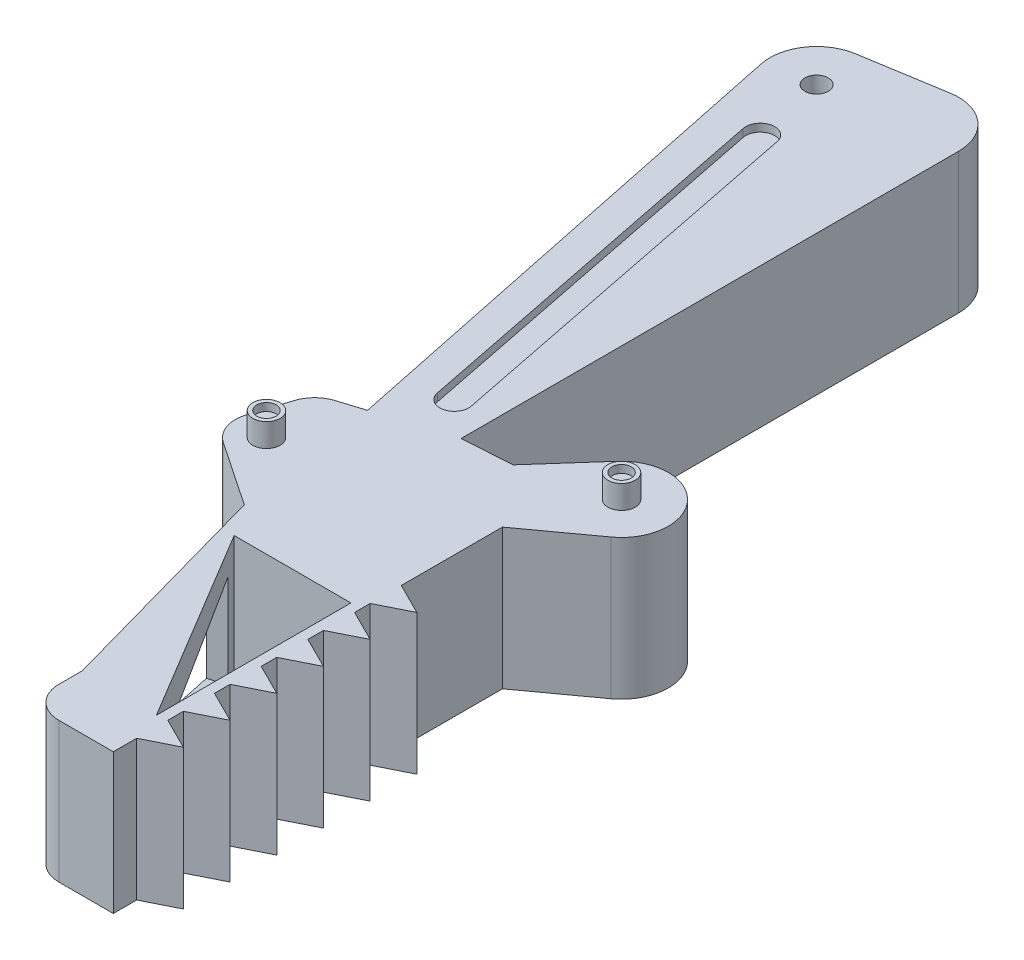
SolidWorks part; units mm, degrees
ref_plane "Front Plane" through (0, 0, 0) normal (0, 0, 1) x (1, 0, 0)
ref_plane "Top Plane" through (0, 0, 0) normal (0, 1, 0) x (1, 0, 0)
ref_plane "Right Plane" through (0, 0, 0) normal (1, 0, 0) x (0, 0, -1)
sketch "Sketch2" plane through (0, 0, 0) normal (0, 1, 0) x (1, 0, 0)
  line L0 (0, 0) -> (-47.8337, 0) construction
  line L4 (-26.3265, -3.8719) -> (-2.6409, 0)
  line L5 (-11.7844, -73.8719) -> (-16.9516, -75.4948)
  line L6 (-16.9516, -75.4948) -> (-19.9749, -85.0269)
  line L7 (-19.9749, -85.0269) -> (-9.1952, -92.2931)
  line L8 (-9.1952, -92.2931) -> (-1.1293, -121.1884)
  line L9 (-1.1293, -121.1884) -> (-1.1293, -128.1884)
  line L10 (-1.1293, -128.1884) -> (9.8707, -128.1884)
  line L11 (9.8707, -128.1884) -> (9.8707, -78.1884)
  line L12 (9.8707, -78.1884) -> (17.9634, -72.3141)
  line L13 (-2.6409, 0) -> (-2.6409, -71)
  line L14 (-2.6409, -71) -> (-11.7844, -73.8719)
  line L15 (-11.7844, -73.8719) -> (-26.3265, -3.8719)
  line L16 (-2.6409, -71) -> (3.6435, -70.5783)
  line L17 (3.6435, -70.5783) -> (9.9527, -63.4743)
  arc A0 (9.9527, -63.4743) -> (17.9634, -72.3141) centre (14.4389, -67.4585) cw
  point P17 (12.9548, -76.5257)
  point P18 (10.1005, -71)
  point P19 (16.4521, -62.391)
  point P20 (17.1505, -78.4257)
  point P22 (11.9758, -79.4186)
  point P23 (11.9386, -62.3885)
  point P24 (10.0167, -77.8819)
  point P25 (-8.9398, -91.899)
  point P26 (-1.1293, -121.1884)
  dimension "D12" = 6
  dimension "D1" = 24
  dimension "D2" = 71
  dimension "D3" = 70
  dimension "D4" = 10
  dimension "D5" = 13
  dimension "D6" = 30
  dimension "D7" = 7
  dimension "D8" = 11
  dimension "D9" = 50
  dimension "D10" = 10
  dimension "D11" = 15
extrude "Boss-Extrude1" add sketch "Sketch2" along normal mid plane 18 contours A0 L17 L16 L14 L5 L6 L7 L8 L9 L10 L11 L12 | L15 L14 L13 L4
fillet "Fillet1" radius 6 2 edges at (-2.6409, 0, 0) (-26.3265, 0, 3.8719)
fillet "Fillet2" radius 4 3 edges at (-1.1293, 0, 128.1884) (-16.9516, 0, 75.4948) (-19.9749, 0, 85.0269)
sketch "Sketch3" plane through (0, 9, 0) normal (0, 1, 0) x (1, 0, 0)
  line L0 (9.8707, -123.1884) -> (13.8707, -123.1884) construction
  line L1 (9.8707, -128.1884) -> (9.8707, -78.1884) construction
  line L2 (2.8707, -128.1884) -> (9.8707, -128.1884) construction
  line L3 (9.8707, -125.1884) -> (9.8707, -121.1884)
  line L4 (9.8707, -121.1884) -> (13.8707, -123.1884)
  line L5 (13.8707, -123.1884) -> (9.8707, -125.1884)
  point P9 (9.8707, -123.1884)
  dimension "D1" = 5
  dimension "D2" = 4
  dimension "D3" = 4
extrude "Boss-Extrude2" add sketch "Sketch3" against normal blind 18
pattern_linear "LPattern1" count 6 spacing 6 along (0, 0, -1) of "Boss-Extrude2"
sketch "Sketch5" plane through (0, 9, 0) normal (0, 1, 0) x (1, 0, 0)
  line L0 (8.5819, -96.3665) -> (-6.4181, -96.3665)
  line L1 (-6.4181, -96.3665) -> (8.5819, -121.3665)
  line L2 (8.5819, -121.3665) -> (8.5819, -96.3665)
  dimension "D1" = 15
  dimension "D2" = 25
extrude "Cut-Extrude1" cut sketch "Sketch5" against normal blind 26
sketch "Sketch6" plane through (-32.431, 0, 9.0528) normal (-0.9632, 0, 0.2689) x (0.2689, 0, 0.9632)
  line L0 (93.4224, 6) -> (93.4224, -6)
  line L1 (93.4224, -6) -> (111.4224, -4.5339)
  line L2 (111.4224, -4.5339) -> (111.4224, 4.5339)
  line L3 (111.4224, 4.5339) -> (93.4224, 6)
  line L4 (86.4224, 9) -> (86.4224, -9) construction
  line L5 (116.4224, 9) -> (116.4224, -9) construction
  line L6 (86.4224, 9) -> (116.4224, 9) construction
  point P6 (86.4224, 0)
  point P7 (93.4224, 0)
  point P10 (116.4224, 0)
  point P11 (111.4224, 0)
  dimension "D1" = 7
  dimension "D2" = 5
  dimension "D3" = 3
extrude "Cut-Extrude2" cut sketch "Sketch6" against normal blind 8
sketch "Sketch7" plane through (0, 9, 0) normal (0, 1, 0) x (1, 0, 0)
  circle A0 centre (-19.1781, -8.783) radius 1.5
  dimension "D1" = 3
extrude "Cut-Extrude3" cut sketch "Sketch7" against normal blind 26
sketch "Sketch8" plane through (0, 9, 0) normal (0, 1, 0) x (1, 0, 0)
  circle A0 centre (14.4389, -67.4585) radius 1.75
  circle A1 centre (-15.2572, -83.3831) radius 1.75
  dimension "D1" = 3.5
extrude "Boss-Extrude3" add sketch "Sketch8" along normal blind 3
sketch "Sketch9" plane through (0, 12, 0) normal (0, 1, 0) x (1, 0, 0)
  circle A2 centre (-15.2572, -83.3831) radius 1.25
  circle A3 centre (-15.2572, -83.3831) radius 1.25
  dimension "D1" = 0.5
extrude "Cut-Extrude4" cut sketch "Sketch9" against normal blind 1
sketch "Sketch10" plane through (0, 12, 0) normal (0, 1, 0) x (1, 0, 0)
  circle A2 centre (14.4389, -67.4585) radius 1.25
  circle A3 centre (14.4389, -67.4585) radius 1.25
  dimension "D1" = 0.5
extrude "Cut-Extrude5" cut sketch "Sketch10" against normal blind 1
sketch "Sketch11" plane through (0, 9, 0) normal (0, 1, 0) x (1, 0, 0)
  line L0 (-17.1966, -18.0056) -> (-7.4101, -67.0949) construction
  line L1 (-15.3753, -17.6425) -> (-5.5888, -66.7318)
  line L2 (-19.0178, -18.3687) -> (-9.2313, -67.4579)
  arc A0 (-15.3753, -17.6425) -> (-19.0178, -18.3687) centre (-17.1966, -18.0056) ccw
  arc A1 (-9.2313, -67.4579) -> (-5.5888, -66.7318) centre (-7.4101, -67.0949) ccw
  point P2 (-12.3033, -42.5502)
extrude "Cut-Extrude6" cut sketch "Sketch11" against normal blind 1
mirror "Mirror1" about plane through (0, 0, 0) normal (0, 1, 0) of "Boss-Extrude3", "Cut-Extrude4", "Cut-Extrude5", "Cut-Extrude6"
